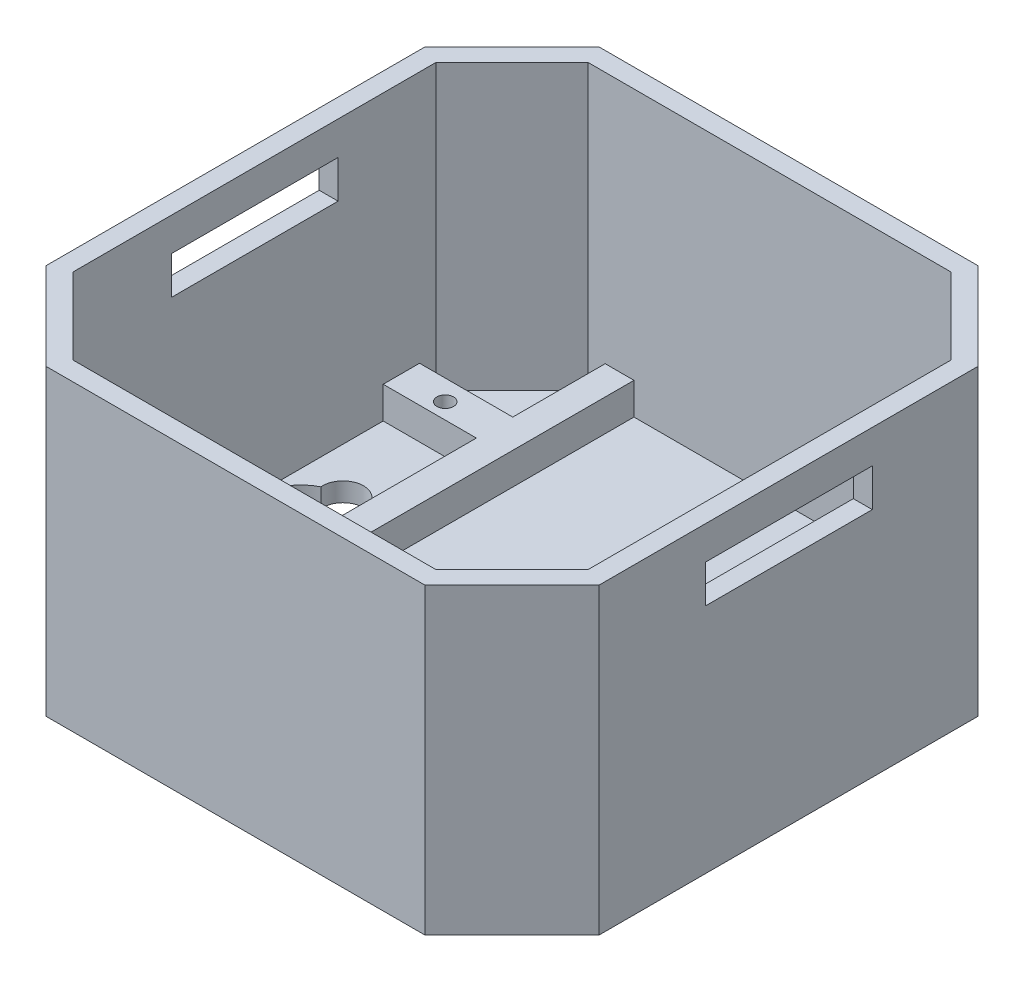
SolidWorks part; units mm, degrees
ref_plane "Alzado" through (0, 0, 0) normal (0, 0, 1) x (1, 0, 0)
ref_plane "Planta" through (0, 0, 0) normal (0, 1, 0) x (1, 0, 0)
ref_plane "Vista lateral" through (0, 0, 0) normal (1, 0, 0) x (0, 0, -1)
sketch "Croquis3" plane through (0, 0, 0) normal (0, 1, 0) x (1, 0, 0)
  line L0 (-25, -32.5) -> (25, -32.5) construction
  line L1 (-25, 32.5) -> (25, 32.5) construction
  line L2 (-25, -32.5) -> (25, 32.5) construction
  line L3 (-25, 32.5) -> (25, -32.5) construction
  line L4 (32.5, 25) -> (32.5, -25) construction
  line L5 (25, -32.5) -> (32.5, -25) construction
  line L6 (32.5, 25) -> (25, 32.5) construction
  line L7 (-32.5, 25) -> (-32.5, -25) construction
  line L8 (-32.5, -25) -> (-25, -32.5) construction
  line L9 (-32.5, 25) -> (-25, 32.5) construction
  line L10 (-25, -32.5) -> (-25, -36.5) construction
  line L11 (-32.5, -25) -> (-36.5, -25) construction
  line L12 (-32.5, 25) -> (-36.5, 25) construction
  line L13 (-25, 32.5) -> (-25, 36.5)
  line L14 (25, 32.5) -> (25, 36.5) construction
  line L15 (32.5, 25) -> (36.5, 25) construction
  line L16 (32.5, -25) -> (36.5, -25) construction
  line L17 (25, -32.5) -> (25, -36.5) construction
  line L18 (-25, -36.5) -> (25, -36.5)
  line L19 (36.5, -25) -> (36.5, 25)
  line L20 (25, 36.5) -> (-25, 36.5)
  line L21 (-36.5, 25) -> (-36.5, -25)
  line L22 (-36.5, -25) -> (-25, -36.5)
  line L23 (-36.5, 25) -> (-25, 36.5)
  line L24 (25, 36.5) -> (36.5, 25)
  line L25 (25, -36.5) -> (36.5, -25)
  point P0 (0, 0)
  point P5 (0, 32.5)
  dimension "D1" = 65
  dimension "D2" = 50
  dimension "D3" = 50
  dimension "D4" = 25
  dimension "D5" = 25
  dimension "D6" = 4
  dimension "D8" = 4
  dimension "D10" = 4
extrude "Saliente-Extruir1" add sketch "Croquis3" along normal blind 40
shell "Vaciado1" thickness 2.5
sketch "Croquis5" plane through (-36.5, 0, 0) normal (-1, 0, 0) x (0, 0, 1)
  line L0 (-25, 40) -> (-25, 0) construction
  line L1 (-11.05, 35.6) -> (10.95, 35.6)
  line L2 (-11.05, 35.6) -> (-11.05, 30.6)
  line L3 (-11.05, 30.6) -> (10.95, 30.6)
  line L4 (10.95, 35.6) -> (10.95, 30.6)
  dimension "D1" = 22
  dimension "D2" = 13.95
  dimension "D3" = 4.4
  dimension "D4" = 5
extrude "Cortar-Extruir1" cut sketch "Croquis5" against normal through all
sketch "Croquis6" plane through (0, 0, 0) normal (0, -1, 0) x (1, 0, 0)
  line L0 (-36.5, 0) -> (-27.9, 0) construction
  line L1 (-36.5, -25) -> (-36.5, 25) construction
  line L2 (0, 0) -> (0, 10.1817) construction
  line L3 (36.5, 0) -> (27.9, 0) construction
  arc A0 (-25.2104, -5.3634) -> (-30.5896, -5.3634) centre (-27.9, 0) ccw
  arc A1 (-30.5896, -5.3634) -> (-25.2104, -5.3634) centre (-27.9, -5.6) ccw
  arc A2 (30.5896, -5.3634) -> (25.2104, -5.3634) centre (27.9, -5.6) cw
  arc A3 (25.2104, -5.3634) -> (30.5896, -5.3634) centre (27.9, 0) cw
  point P8 (-27.9, -8.3)
  point P16 (27.9, -8.3)
  dimension "D2" = 12
  dimension "D4" = 5.4
  dimension "D1" = 8.6
  dimension "D3" = 8.3
extrude "Cortar-Extruir2" cut sketch "Croquis6" against normal blind 10
sketch "Croquis7" plane through (0, 2.5, 0) normal (0, 1, 0) x (1, 0, 0)
  line L0 (-33.9, 0) -> (-21.7, 0) construction
  line L1 (-33.9, 0) -> (-17.9, 0) construction
  line L2 (-21.7, 0) -> (-21.7, 17)
  line L3 (23.9645, 34) -> (-23.9645, 34) construction
  line L4 (-21.7, 0) -> (-21.7, -6)
  line L5 (-23.9645, -34) -> (23.9645, -34) construction
  line L6 (-17.9, -34) -> (-17.9, 34)
  line L7 (-23.9645, -34) -> (23.9645, -34) construction
  line L8 (-17.9, 34) -> (-21.7, 34)
  line L9 (-21.7, -34) -> (-17.9, -34)
  line L10 (-27.9, -6) -> (-27.9, 16.7) construction
  line L11 (-21.7, 17) -> (-34, 17)
  line L12 (-34, 23.9645) -> (-34, -23.9645) construction
  line L13 (-21.7, 21.8) -> (-34, 21.8)
  line L14 (-34, 21.8) -> (-34, 17)
  line L15 (-21.7, -6) -> (-34, -6)
  line L16 (-21.7, -10.8) -> (-34, -10.8)
  line L17 (-34, 23.9645) -> (-34, -23.9645) construction
  line L18 (-34, -6) -> (-34, -10.8)
  line L19 (-21.7, 21.8) -> (-21.7, 34)
  line L20 (-21.7, -10.8) -> (-21.7, -15.8)
  line L21 (0, 0) -> (0, 8.7272) construction
  line L22 (27.9, -6) -> (27.9, 16.7) construction
  line L23 (33.9, 0) -> (17.9, 0) construction
  line L24 (33.9, 0) -> (21.7, 0) construction
  line L25 (21.7, -19.8) -> (21.7, -34)
  line L26 (34, -15.8) -> (34, -19.8)
  line L27 (21.7, -19.8) -> (34, -19.8)
  line L28 (34, -15.8) -> (21.7, -15.8)
  line L29 (21.7, -10.8) -> (21.7, -15.8)
  line L30 (21.7, 21.8) -> (21.7, 34)
  line L31 (34, -6) -> (34, -10.8)
  line L32 (21.7, -10.8) -> (34, -10.8)
  line L33 (21.7, -6) -> (34, -6)
  line L34 (34, 21.8) -> (34, 17)
  line L35 (21.7, 21.8) -> (34, 21.8)
  line L36 (21.7, 17) -> (34, 17)
  line L37 (21.7, -34) -> (17.9, -34)
  line L38 (-34, -15.8) -> (-21.7, -15.8)
  line L39 (-34, -19.8) -> (-34, -23.9645)
  line L40 (-34, -15.8) -> (-34, -19.8)
  line L41 (-34, -23.9645) -> (-23.9645, -34)
  line L42 (17.9, 34) -> (21.7, 34)
  line L43 (17.9, -34) -> (17.9, 34)
  line L44 (21.7, 0) -> (21.7, -6)
  line L45 (21.7, 0) -> (21.7, 17)
  line L46 (-23.9645, -34) -> (-21.7, -34)
  arc A0 (-30.5896, 5.3634) -> (-25.2104, 5.3634) centre (-27.9, 0) ccw construction
  dimension "D1" = 12.2
  dimension "D2" = 16
  dimension "D3" = 22.7
  dimension "D4" = 4.8
  dimension "D5" = 4.8
  dimension "D6" = 5
  dimension "D7" = 4
extrude "Saliente-Extruir4" add sketch "Croquis7" along normal blind 4.2
sketch "Croquis9" plane through (0, 2.5, 0) normal (0, 1, 0) x (1, 0, 0)
  line L0 (0, 0) -> (0, 6.8473) construction
  line L1 (-21.7, -10.8) -> (-34, -10.8)
  line L2 (-21.7, -10.8) -> (-21.7, -15.8)
  line L3 (-21.7, -15.8) -> (-34, -15.8)
  line L4 (-34, -10.8) -> (-34, -15.8)
  line L5 (34, -10.8) -> (34, -15.8)
  line L6 (21.7, -15.8) -> (34, -15.8)
  line L7 (21.7, -10.8) -> (21.7, -15.8)
  line L8 (21.7, -10.8) -> (34, -10.8)
extrude "Cortar-Extruir3" cut sketch "Croquis9" against normal through all
sketch "Croquis10" plane through (0, 6.7, 0) normal (0, 1, 0) x (1, 0, 0)
  circle A0 centre (-24.9, -22.8) radius 6
  point P2 (-24.4675, -22.9912)
  dimension "D1" = 12
  dimension "D2" = 7
  dimension "D3" = 7
extrude "Cortar-Extruir4" cut sketch "Croquis10" against normal blind 4
sketch "Croquis11" plane through (0, 2.7, 0) normal (0, 1, 0) x (1, 0, 0)
  circle A0 centre (-24.9, -22.8) radius 2.75
  dimension "D1" = 5.5
extrude "Cortar-Extruir5" cut sketch "Croquis11" against normal blind 4
sketch "Croquis12" plane through (0, 6.7, 0) normal (0, 1, 0) x (1, 0, 0)
  line L0 (-34, 23.9645) -> (-34, -23.9645) construction
  line L1 (0, 0) -> (0, 8.3797) construction
  circle A0 centre (-27.91, 19.1) radius 1.1
  circle A1 centre (-27.91, -8.7) radius 1.1
  circle A2 centre (27.91, -8.7) radius 1.1
  circle A3 centre (27.91, 19.1) radius 1.1
  dimension "D3" = 2.2
  dimension "D5" = 2.2
  dimension "D1" = 6.09
  dimension "D2" = 2.7
  dimension "D4" = 2.7
  dimension "D6" = 6.09
extrude "Cortar-Extruir6" cut sketch "Croquis12" against normal blind 6
